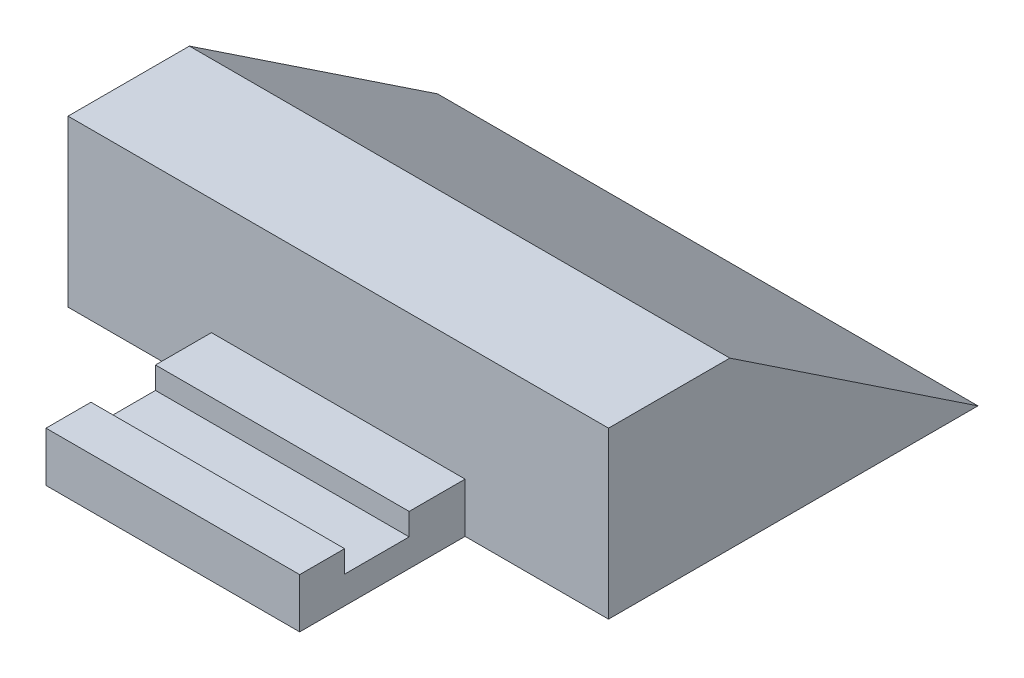
SolidWorks part; units mm, degrees
ref_plane "Front" through (0, 0, 0) normal (0, 0, 1) x (1, 0, 0)
ref_plane "Top" through (0, 0, 0) normal (0, 1, 0) x (1, 0, 0)
ref_plane "Right" through (0, 0, 0) normal (1, 0, 0) x (0, 0, -1)
sketch "Эскиз1" plane through (0, 0, 0) normal (0, 1, 0) x (1, 0, 0)
  line L0 (0, 0) -> (0, 134.0849) construction
  line L1 (-49, 100) -> (49, 100)
  line L2 (49, 100) -> (49, 32)
  line L3 (49, 32) -> (23, 32)
  line L4 (23, 32) -> (23, 2)
  line L5 (23, 2) -> (-23, 2)
  line L6 (-23, 32) -> (-23, 2)
  line L7 (-49, 32) -> (-23, 32)
  line L8 (-49, 100) -> (-49, 32)
  point P10 (0, 2)
  point P13 (0, 100)
  dimension "D1" = 98
  dimension "D2" = 100
  dimension "D3" = 2
  dimension "D4" = 32
  dimension "D5" = 46
extrude "Бобышка-Вытянуть1" add sketch "Эскиз1" along normal blind 30
sketch "Эскиз2" plane through (-49, 0, 0) normal (-1, 0, 0) x (0, 0, 1)
  line L0 (0, 0) -> (0, 41.1559) construction
  line L1 (-99, 0) -> (-54, 30)
  line L2 (-100, 0) -> (-32, 0) construction
  line L3 (0, 0) -> (-112.3908, 0) construction
  line L4 (-100, 30) -> (-32, 30) construction
  line L5 (-54, 30) -> (-54, 44.9028)
  line L6 (-54, 44.9028) -> (-113.2555, 44.9028)
  line L7 (-113.2555, 44.9028) -> (-113.2555, 0)
  line L8 (-113.2555, 0) -> (-99, 0)
  dimension "D1" = 99
  dimension "D2" = 45
extrude "Вырез-Вытянуть1" cut sketch "Эскиз2" against normal up to surface (98 mm away) up to face at (49, 15, -66)
sketch "Эскиз3" plane through (0, 30, 0) normal (0, 1, 0) x (1, 0, 0)
  line L0 (0, 0) -> (0, 45.9775) construction
  line L1 (0, 0) -> (62.9459, 0) construction
  line L2 (0, 16) -> (40.9794, 16) construction
  line L3 (23, 21.85) -> (-23, 21.85)
  line L4 (23, 2) -> (23, 32) construction
  line L5 (-23, 32) -> (-23, 2) construction
  line L6 (23, 10.15) -> (-23, 10.15)
  line L7 (23, 21.85) -> (23, 10.15)
  line L8 (-23, 21.85) -> (-23, 10.15)
  dimension "D1" = 16
  dimension "D2" = 11.7
extrude "Вырез-Вытянуть2" cut sketch "Эскиз3" against normal blind 25
sketch "Эскиз4" plane through (-23, 0, 0) normal (-1, 0, 0) x (0, 0, 1)
  line L0 (-32, 9) -> (1.0795, 9)
  line L1 (-32, 30) -> (-32, 0) construction
  line L2 (1.0795, 9) -> (1.0795, 31.9748)
  line L3 (1.0795, 31.9748) -> (-32, 31.9748)
  line L4 (-32, 31.9748) -> (-32, 9)
  dimension "D1" = 9
extrude "Вырез-Вытянуть3" cut sketch "Эскиз4" against normal up to surface (46 mm away) up to face at (23, 16.25, -16.5)
